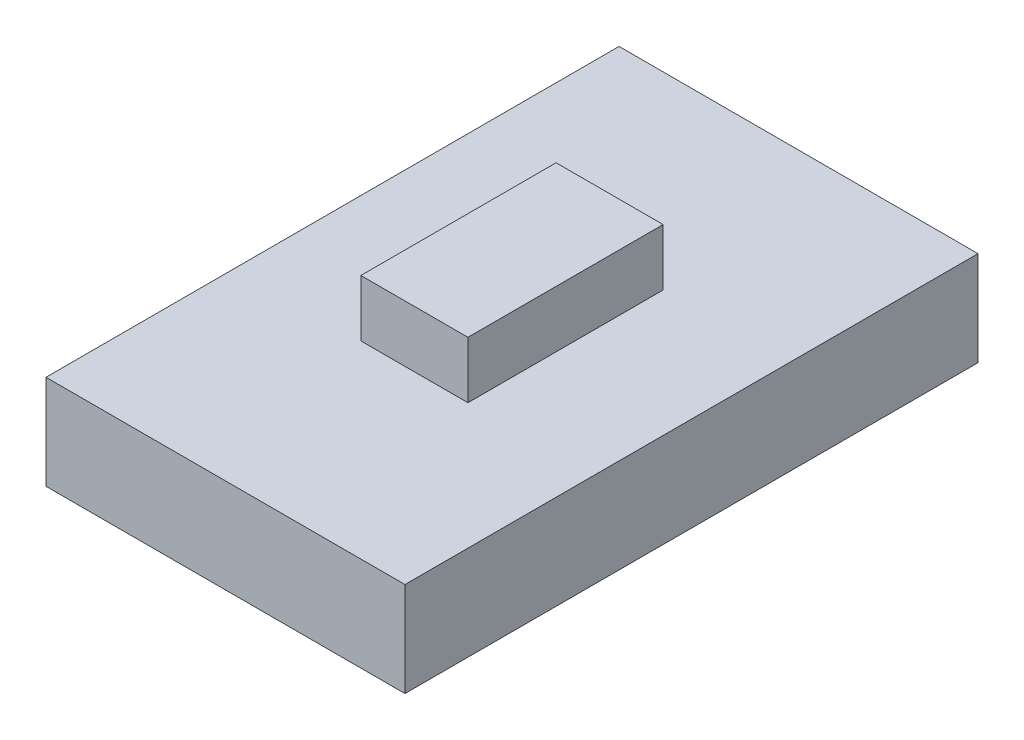
SolidWorks part; units mm, degrees
ref_plane "Front Plane" through (0, 0, 0) normal (0, 0, 1) x (1, 0, 0)
ref_plane "Top Plane" through (0, 0, 0) normal (0, 1, 0) x (1, 0, 0)
ref_plane "Right Plane" through (0, 0, 0) normal (1, 0, 0) x (0, 0, -1)
sketch "Sketch1" plane through (0, 0, 0) normal (0, 1, 0) x (1, 0, 0)
  line L0 (0, 0) -> (0, 1.55)
  line L1 (0, 1.55) -> (0.85, 1.55)
  line L2 (0.85, 1.55) -> (0.85, 0)
  line L3 (0.85, 0) -> (0, 0)
extrude "Boss-Extrude1" add sketch "Sketch1" along normal blind 0.45
sketch "Sketch2" plane through (0, 0, 0) normal (0, -1, 0) x (1, 0, 0)
  line L8 (0.425, 1.5) -> (-1, 1.5)
  line L9 (-1, 1.5) -> (-1, -3.05)
  line L10 (-1, -3.05) -> (1.85, -3.05)
  line L11 (1.85, -3.05) -> (1.85, 1.5)
  line L12 (1.85, 1.5) -> (0.425, 1.5)
extrude "Boss-Extrude2" add sketch "Sketch2" along normal blind 0.75
